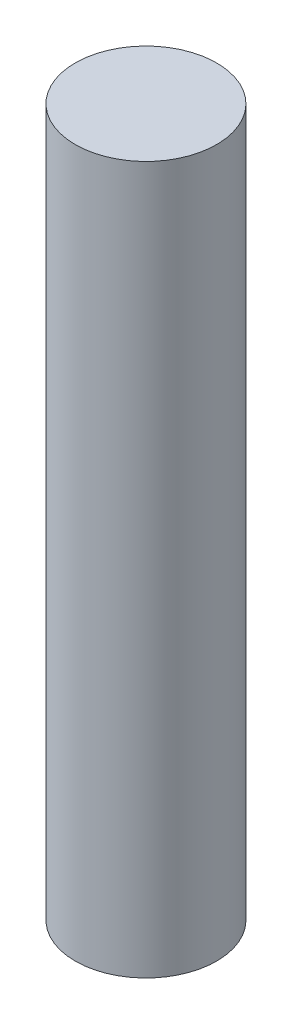
SolidWorks part; units mm, degrees
ref_plane "Front Plane" through (0, 0, 0) normal (0, 0, 1) x (1, 0, 0)
ref_plane "Top Plane" through (0, 0, 0) normal (0, 1, 0) x (1, 0, 0)
ref_plane "Right Plane" through (0, 0, 0) normal (1, 0, 0) x (0, 0, -1)
sketch "Sketch1" plane through (0, 0, 0) normal (0, 1, 0) x (1, 0, 0)
  circle A0 centre (0, 0) radius 0.1
  dimension "D1" = 0.2
extrude "Boss-Extrude1" add sketch "Sketch1" along normal blind 1
